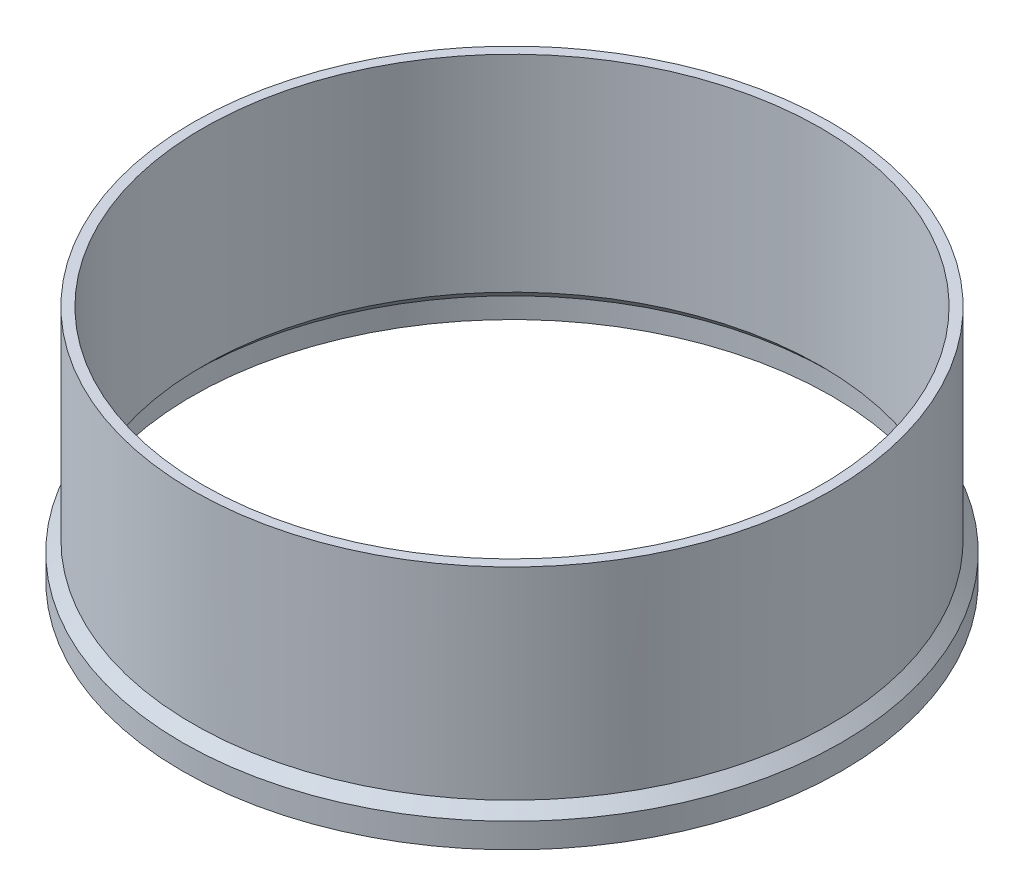
SolidWorks part; units mm, degrees
ref_plane "Front Plane" through (0, 0, 0) normal (0, 0, 1) x (1, 0, 0)
ref_plane "Top Plane" through (0, 0, 0) normal (0, 1, 0) x (1, 0, 0)
ref_plane "Right Plane" through (0, 0, 0) normal (1, 0, 0) x (0, 0, -1)
sketch "Sketch1" plane through (0, 0, 0) normal (0, 1, 0) x (1, 0, 0)
  circle A0 centre (0, 0) radius 75
  circle A1 centre (0, 0) radius 77.4
  dimension "D1" = 150
  dimension "D2" = 2.4
extrude "Boss-Extrude1" add sketch "Sketch1" along normal blind 50
sketch "Sketch3" plane through (0, 0, 0) normal (0, 0, 1) x (1, 0, 0)
  line L0 (0, 0) -> (0, 74.435) construction
sketch "Sketch4" plane through (0, 0, 0) normal (0, 0, 1) x (1, 0, 0)
  line L0 (75, 0) -> (77.6, -2.6)
  line L1 (0, 0) -> (75, 0) construction
  line L2 (80, -1.6059) -> (77.4, 0.9941)
  line L3 (77.6, 0) -> (77.6, -2.6) construction
  line L5 (77.6, -2.6) -> (77.6, -7.6)
  line L6 (77.6, -7.6) -> (80, -7.6)
  line L7 (80, -7.6) -> (80, -1.6059)
  line L9 (77.4, 0) -> (77.4, 50) construction
  line L11 (77.4, 0.9941) -> (77.4, 0)
  line L12 (77.4, 0) -> (75, 0)
  point P1 (87.1111, -12.1111)
  point P7 (76.6971, 1.6971)
  point P8 (88.8081, -10.414)
  dimension "D1" = 77.6
  dimension "D3" = 2.4
  dimension "D2" = 2.4
revolve "Revolve1" add sketch "Sketch4" angle 360 about L0
